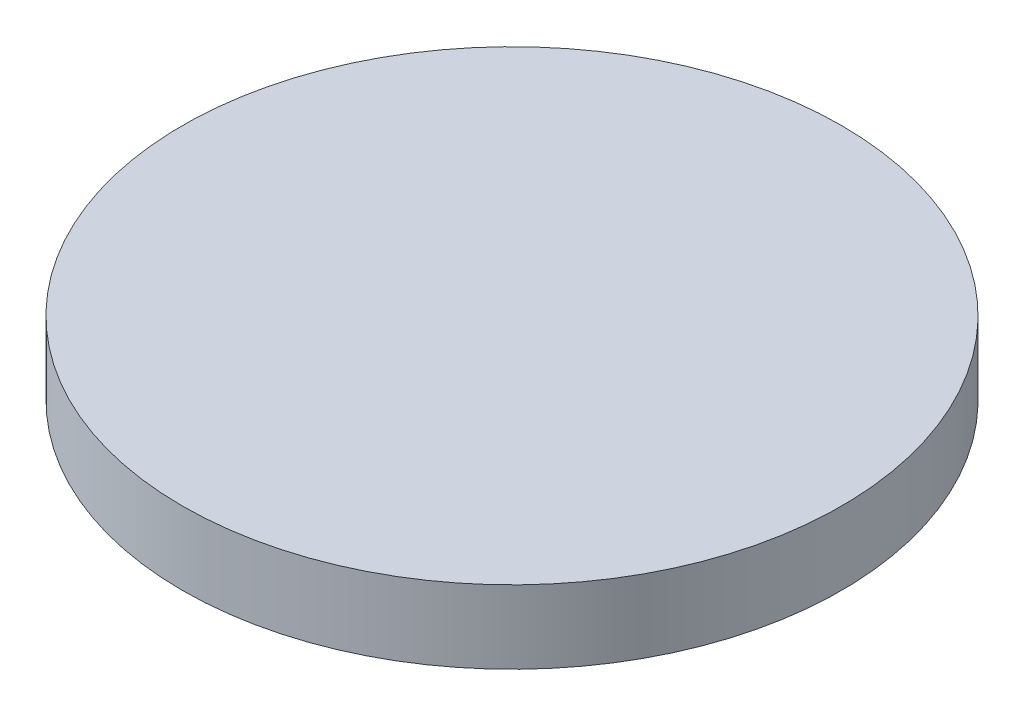
SolidWorks part; units mm, degrees
ref_plane "Front Plane" through (0, 0, 0) normal (0, 0, 1) x (1, 0, 0)
ref_plane "Top Plane" through (0, 0, 0) normal (0, 1, 0) x (1, 0, 0)
ref_plane "Right Plane" through (0, 0, 0) normal (1, 0, 0) x (0, 0, -1)
sketch "Sketch1" plane through (0, 0, 0) normal (1, 0, 0) x (0, 0, -1)
  line L0 (-11, 0) -> (0, 0)
  line L1 (0, 0) -> (0, 2.5)
  line L2 (-5.5, 0) -> (-5.5, 5.1327) construction
  line L3 (-11, 0) -> (-11, 2.5)
  line L4 (-5.5, 0) -> (-5.5, 2.2189)
  spline S0 degree 2 poles (-11, 2.5) (-5.5, 1.9379) (0, 2.5) knots 0 0 0 1 1 1
  dimension "D1" = 11
  dimension "D2" = 2.5
revolve "Revolve-Thin1" add sketch "Sketch1" angle 360 about L2
